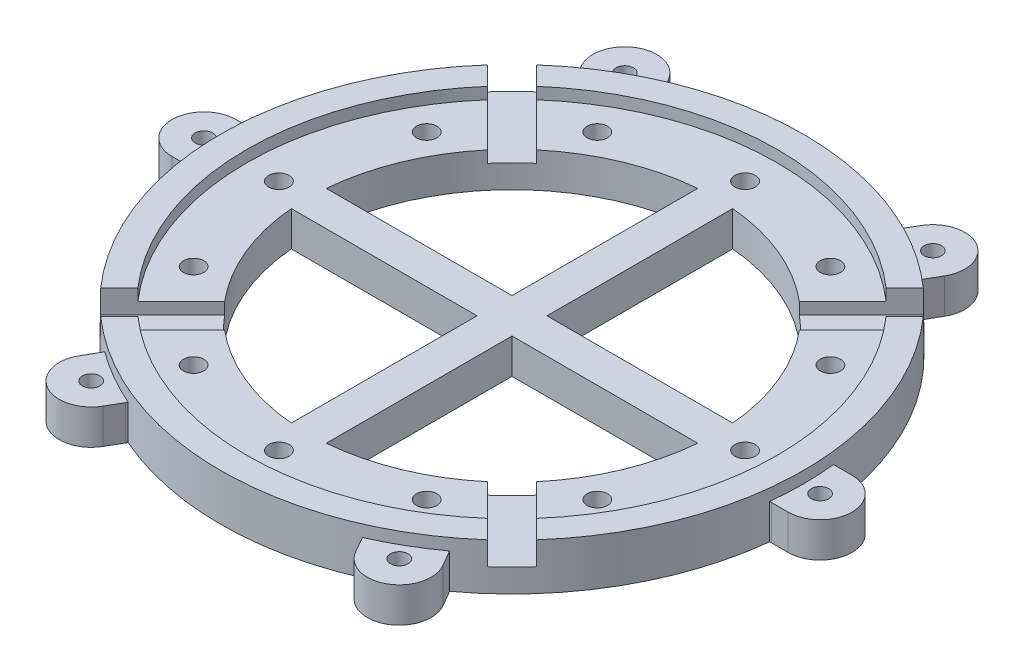
SolidWorks part; units mm, degrees
ref_plane "Front Plane" through (0, 0, 0) normal (0, 0, 1) x (1, 0, 0)
ref_plane "Top Plane" through (0, 0, 0) normal (0, 1, 0) x (1, 0, 0)
ref_plane "Right Plane" through (0, 0, 0) normal (1, 0, 0) x (0, 0, -1)
sketch "Sketch1" plane through (0, 0, 0) normal (0, 1, 0) x (1, 0, 0)
  circle A0 centre (0, 0) radius 50
  dimension "D1" = 100
extrude "Boss-Extrude1" add sketch "Sketch1" along normal blind 8
sketch "Sketch2" plane through (0, 8, 0) normal (0, 1, 0) x (1, 0, 0)
  circle A0 centre (0, 0) radius 45.5
  dimension "D1" = 91
extrude "Cut-Extrude1" cut sketch "Sketch2" against normal blind 2
sketch "Sketch3" plane through (0, 0, 0) normal (0, -1, 0) x (1, 0, 0)
  line L0 (0, 0) -> (-54.3429, 0) construction
  line L1 (0, 0) -> (0, 63.8029) construction
  circle A0 centre (0, 0) radius 40 construction
  circle A1 centre (-40, 0) radius 1.75
  circle A2 centre (-34.641, 20) radius 1.75
  circle A3 centre (-20, 34.641) radius 1.75
  circle A4 centre (0, 40) radius 1.75
  circle A5 centre (20, 34.641) radius 1.75
  circle A6 centre (34.641, 20) radius 1.75
  circle A7 centre (40, 0) radius 1.75
  circle A8 centre (34.641, -20) radius 1.75
  circle A9 centre (20, -34.641) radius 1.75
  circle A10 centre (0, -40) radius 1.75
  circle A11 centre (-20, -34.641) radius 1.75
  circle A12 centre (-34.641, -20) radius 1.75
  point P31 (0, 0)
  dimension "D1" = 80
  dimension "D2" = 3.5
  dimension "D3" = 12
extrude "Cut-Extrude2" cut sketch "Sketch3" against normal through all
sketch "Sketch4" plane through (0, 0, 0) normal (0, -1, 0) x (1, 0, 0)
  line L0 (0, 0) -> (-52.7979, 0) construction
  circle A0 centre (0, 0) radius 40 construction
  circle A1 centre (-40, 0) radius 3.25
  circle A2 centre (-34.641, 20) radius 3.25
  circle A3 centre (-20, 34.641) radius 3.25
  circle A4 centre (0, 40) radius 3.25
  circle A5 centre (20, 34.641) radius 3.25
  circle A6 centre (34.641, 20) radius 3.25
  circle A7 centre (40, 0) radius 3.25
  circle A8 centre (34.641, -20) radius 3.25
  circle A9 centre (20, -34.641) radius 3.25
  circle A10 centre (0, -40) radius 3.25
  circle A11 centre (-20, -34.641) radius 3.25
  circle A12 centre (-34.641, -20) radius 3.25
  point P31 (0, 0)
  dimension "D1" = 6.5
  dimension "D2" = 12
extrude "Cut-Extrude3" cut sketch "Sketch4" against normal blind 3
sketch "Sketch5" plane through (0, 0, 0) normal (0, -1, 0) x (1, 0, 0)
  line L0 (0, 0) -> (73.7843, 0) construction
  line L1 (50, 0) -> (52.8721, 0) construction
  line L2 (50, 5.4814) -> (52.8721, 5.4814)
  line L3 (50, -5.4814) -> (52.8721, -5.4814)
  line L4 (29.747, -40.5606) -> (31.183, -43.0479)
  line L5 (20.253, -46.042) -> (21.689, -48.5292)
  line L6 (25, -43.3013) -> (26.436, -45.7885) construction
  line L7 (-20.253, -46.042) -> (-21.689, -48.5292)
  line L8 (-29.747, -40.5606) -> (-31.183, -43.0479)
  line L9 (-25, -43.3013) -> (-26.436, -45.7885) construction
  line L10 (-50, -5.4814) -> (-52.8721, -5.4814)
  line L11 (-50, 5.4814) -> (-52.8721, 5.4814)
  line L12 (-50, 0) -> (-52.8721, 0) construction
  line L13 (-29.747, 40.5606) -> (-31.183, 43.0479)
  line L14 (-20.253, 46.042) -> (-21.689, 48.5292)
  line L15 (-25, 43.3013) -> (-26.436, 45.7885) construction
  line L16 (20.253, 46.042) -> (21.689, 48.5292)
  line L17 (29.747, 40.5606) -> (31.183, 43.0479)
  line L18 (25, 43.3013) -> (26.436, 45.7885) construction
  circle A0 centre (0, 0) radius 50 construction
  arc A1 (50, 5.4814) -> (49.6995, 5.4731) centre (50, 0) ccw
  arc A2 (52.8721, -5.4814) -> (52.8721, 5.4814) centre (52.8721, 0) ccw
  arc A3 (49.6995, -5.4731) -> (49.6995, 5.4731) centre (0, 0) ccw
  arc A4 (49.6995, -5.4731) -> (50, -5.4814) centre (50, 0) ccw
  arc A5 (29.747, -40.5606) -> (29.5896, -40.3045) centre (25, -43.3013) ccw
  arc A6 (21.689, -48.5292) -> (31.183, -43.0479) centre (26.436, -45.7885) ccw
  arc A7 (20.1099, -45.7776) -> (29.5896, -40.3045) centre (0, 0) ccw
  arc A8 (20.1099, -45.7776) -> (20.253, -46.042) centre (25, -43.3013) ccw
  arc A9 (-20.253, -46.042) -> (-20.1099, -45.7776) centre (-25, -43.3013) ccw
  arc A10 (-31.183, -43.0479) -> (-21.689, -48.5292) centre (-26.436, -45.7885) ccw
  arc A11 (-29.5896, -40.3045) -> (-20.1099, -45.7776) centre (0, 0) ccw
  arc A12 (-29.5896, -40.3045) -> (-29.747, -40.5606) centre (-25, -43.3013) ccw
  arc A13 (-50, -5.4814) -> (-49.6995, -5.4731) centre (-50, 0) ccw
  arc A14 (-52.8721, 5.4814) -> (-52.8721, -5.4814) centre (-52.8721, 0) ccw
  arc A15 (-49.6995, 5.4731) -> (-49.6995, -5.4731) centre (0, 0) ccw
  arc A16 (-49.6995, 5.4731) -> (-50, 5.4814) centre (-50, 0) ccw
  arc A17 (-29.747, 40.5606) -> (-29.5896, 40.3045) centre (-25, 43.3013) ccw
  arc A18 (-21.689, 48.5292) -> (-31.183, 43.0479) centre (-26.436, 45.7885) ccw
  arc A19 (-20.1099, 45.7776) -> (-29.5896, 40.3045) centre (0, 0) ccw
  arc A20 (-20.1099, 45.7776) -> (-20.253, 46.042) centre (-25, 43.3013) ccw
  arc A21 (20.253, 46.042) -> (20.1099, 45.7776) centre (25, 43.3013) ccw
  arc A22 (31.183, 43.0479) -> (21.689, 48.5292) centre (26.436, 45.7885) ccw
  arc A23 (29.5896, 40.3045) -> (20.1099, 45.7776) centre (0, 0) ccw
  arc A24 (29.5896, 40.3045) -> (29.747, 40.5606) centre (25, 43.3013) ccw
  point P7 (51.436, 0)
  point P18 (25.718, -44.5449)
  point P27 (-25.718, -44.5449)
  point P36 (-51.436, 0)
  point P45 (-25.718, 44.5449)
  point P54 (25.718, 44.5449)
  point P61 (0, 0)
  dimension "D1" = 6
extrude "Boss-Extrude2" add sketch "Sketch5" against normal blind 6
sketch "Sketch6" plane through (0, 0, 0) normal (0, -1, 0) x (1, 0, 0)
  line L0 (0, 0) -> (75.9894, 0) construction
  circle A0 centre (52.8721, 0) radius 1.5
  circle A1 centre (26.436, -45.7885) radius 1.5
  circle A2 centre (-26.436, -45.7885) radius 1.5
  circle A3 centre (-52.8721, 0) radius 1.5
  circle A4 centre (-26.436, 45.7885) radius 1.5
  circle A5 centre (26.436, 45.7885) radius 1.5
  point P18 (0, 0)
  dimension "D1" = 3
  dimension "D2" = 6
extrude "Cut-Extrude4" cut sketch "Sketch6" against normal through all
sketch "Sketch9" plane through (0, 6, 0) normal (0, 1, 0) x (1, 0, 0)
  line L0 (0, 0) -> (0, -55.2199) construction
  line L1 (0, 0) -> (-68.759, 0) construction
  line L2 (-3, -3) -> (-3, -34.8712)
  line L3 (-3, -3) -> (-34.8712, -3)
  line L4 (-3, 3) -> (-34.8712, 3)
  line L5 (-3, 3) -> (-3, 34.8712)
  line L6 (3, 3) -> (3, 34.8712)
  line L7 (3, 3) -> (34.8712, 3)
  line L8 (3, -3) -> (34.8712, -3)
  line L9 (3, -3) -> (3, -34.8712)
  arc A0 (-34.8712, -3) -> (-3, -34.8712) centre (0, 0) ccw
  arc A1 (-3, 34.8712) -> (-34.8712, 3) centre (0, 0) ccw
  arc A2 (34.8712, 3) -> (3, 34.8712) centre (0, 0) ccw
  arc A3 (3, -34.8712) -> (34.8712, -3) centre (0, 0) ccw
  point P8 (0, -27.6099)
  point P20 (0, 0)
  dimension "D1" = 70
  dimension "D2" = 3
  dimension "D3" = 3
  dimension "D4" = 4
extrude "Cut-Extrude6" cut sketch "Sketch9" against normal through all
sketch "Sketch10" plane through (0, 8, 0) normal (0, 1, 0) x (1, 0, 0)
  line L0 (0, 0) -> (-49.2881, 49.2881) construction
  line L1 (0, 0) -> (0, 76.1612) construction
  line L2 (0, 0) -> (-35.3553, 35.3553) construction
  line L3 (-24.0548, 19.8122) -> (-37.4767, 33.234)
  line L4 (-19.8122, 24.0548) -> (-33.234, 37.4767)
  line L5 (0, 0) -> (35.3553, 35.3553) construction
  line L6 (19.8122, 24.0548) -> (33.234, 37.4767)
  line L7 (24.0548, 19.8122) -> (37.4767, 33.234)
  line L8 (0, 0) -> (35.3553, -35.3553) construction
  line L9 (24.0548, -19.8122) -> (37.4767, -33.234)
  line L10 (19.8122, -24.0548) -> (33.234, -37.4767)
  line L11 (0, 0) -> (-35.3553, -35.3553) construction
  line L12 (-19.8122, -24.0548) -> (-33.234, -37.4767)
  line L13 (-24.0548, -19.8122) -> (-37.4767, -33.234)
  circle A0 centre (0, 0) radius 50 construction
  arc A1 (-24.0548, -19.8122) -> (-19.8122, -24.0548) centre (0, 0) ccw
  arc A2 (-33.234, 37.4767) -> (-37.4767, 33.234) centre (-35.3553, 35.3553) ccw
  arc A3 (19.8122, -24.0548) -> (24.0548, -19.8122) centre (0, 0) ccw
  arc A4 (37.4767, 33.234) -> (33.234, 37.4767) centre (35.3553, 35.3553) ccw
  arc A5 (24.0548, 19.8122) -> (19.8122, 24.0548) centre (0, 0) ccw
  arc A6 (33.234, -37.4767) -> (37.4767, -33.234) centre (35.3553, -35.3553) ccw
  arc A7 (-19.8122, 24.0548) -> (-24.0548, 19.8122) centre (0, 0) ccw
  arc A8 (-37.4767, -33.234) -> (-33.234, -37.4767) centre (-35.3553, -35.3553) ccw
  point P3 (-17.6777, 17.6777)
  point P14 (-17.6777, -17.6777)
  point P16 (17.6777, 17.6777)
  point P23 (17.6777, -17.6777)
  point P30 (-17.6777, -17.6777)
  point P36 (0, 0)
  point P44 (17.6777, 17.6777)
  dimension "D1" = 45
  dimension "D2" = 6
extrude "Cut-Extrude9" cut sketch "Sketch10" against normal blind 4
